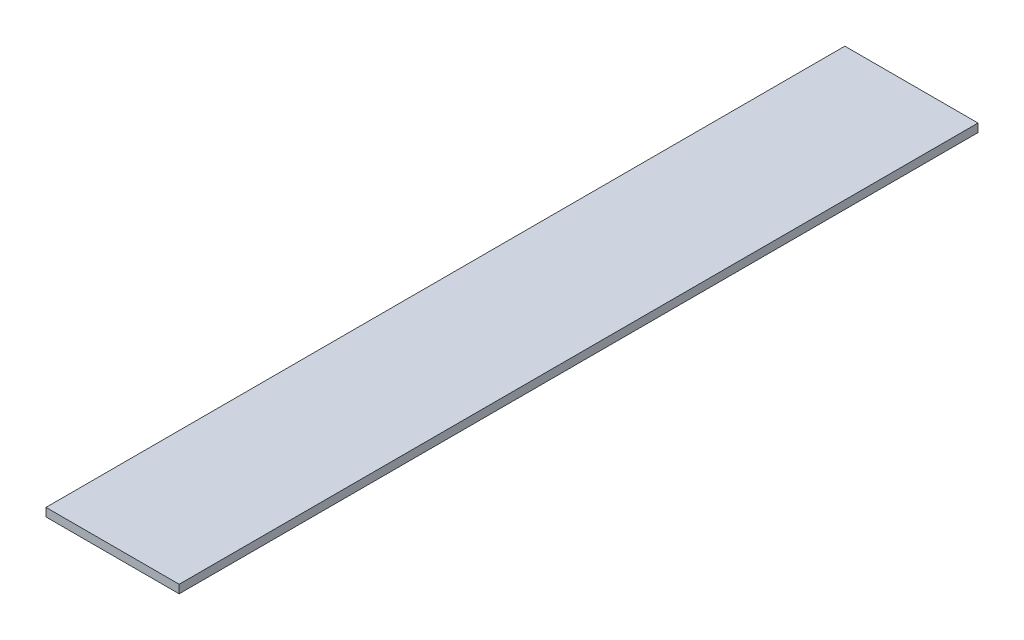
SolidWorks part; units mm, degrees
ref_plane "Front Plane" through (0, 0, 0) normal (0, 0, 1) x (1, 0, 0)
ref_plane "Top Plane" through (0, 0, 0) normal (0, 1, 0) x (1, 0, 0)
ref_plane "Right Plane" through (0, 0, 0) normal (1, 0, 0) x (0, 0, -1)
sketch "Sketch1" plane through (0, 0, 0) normal (0, 0, 1) x (1, 0, 0)
  line L1 (-25.4, 1.5875) -> (25.4, 1.5875)
  line L2 (-25.4, 1.5875) -> (-25.4, -1.5875)
  line L3 (-25.4, -1.5875) -> (25.4, -1.5875)
  line L4 (25.4, 1.5875) -> (25.4, -1.5875)
  line L5 (-25.4, 1.5875) -> (25.4, -1.5875) construction
  line L6 (-25.4, -1.5875) -> (25.4, 1.5875) construction
  point P0 (0, 0)
  dimension "D1" = 50.8
  dimension "D2" = 3.175
extrude "Boss-Extrude1" add sketch "Sketch1" along normal blind 304.8
